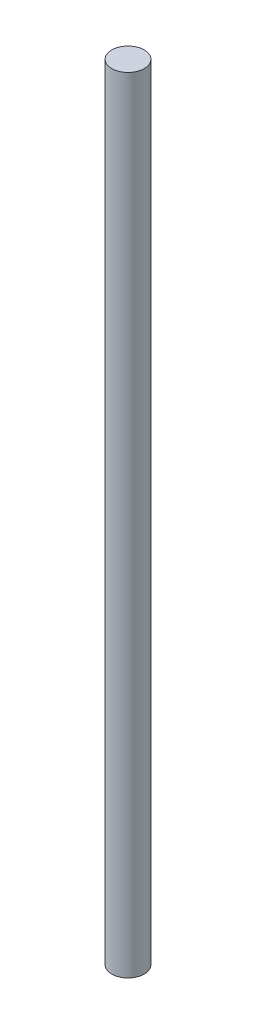
SolidWorks part; units mm, degrees
ref_plane "Front Plane" through (0, 0, 0) normal (0, 0, 1) x (1, 0, 0)
ref_plane "Top Plane" through (0, 0, 0) normal (0, 1, 0) x (1, 0, 0)
ref_plane "Right Plane" through (0, 0, 0) normal (1, 0, 0) x (0, 0, -1)
sketch "Sketch1" plane through (0, 0, 0) normal (0, 1, 0) x (1, 0, 0)
  circle A0 centre (0, 0) radius 2.5
  dimension "D1" = 5
extrude "Boss-Extrude1" add sketch "Sketch1" along normal blind 121
